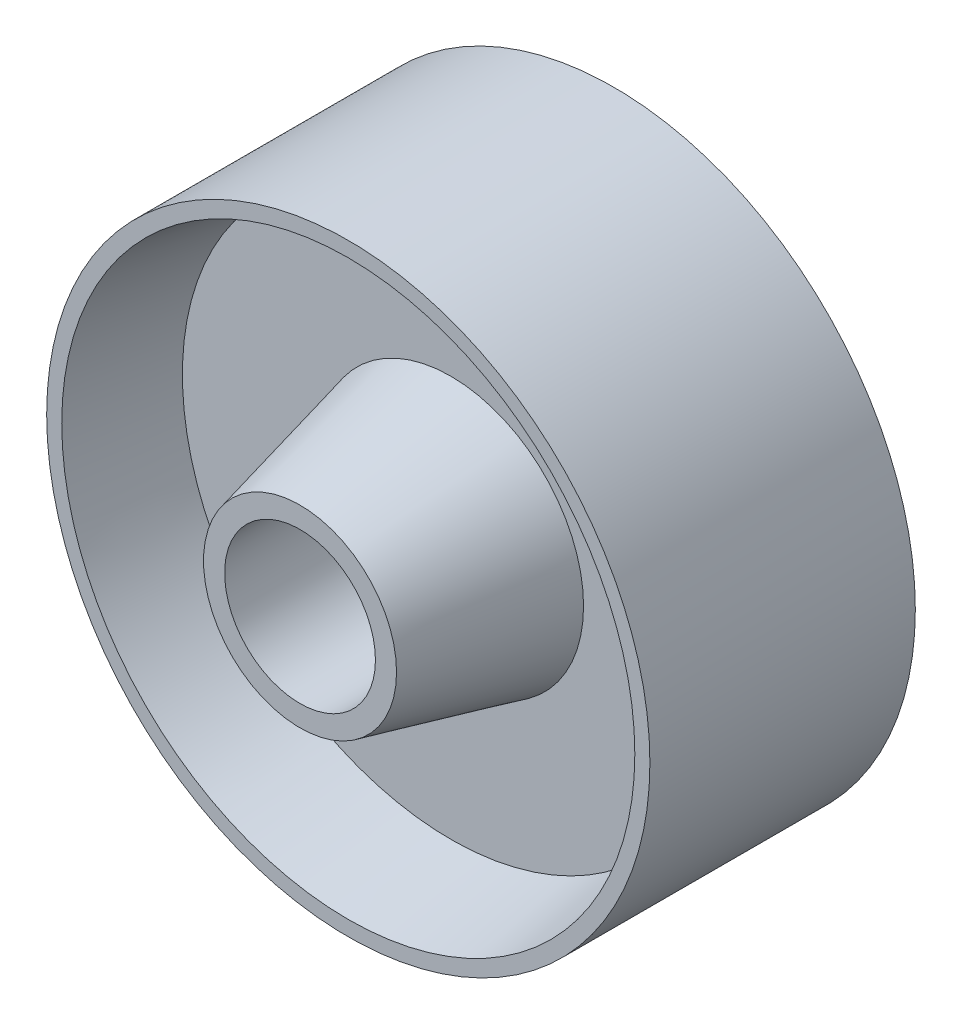
SolidWorks part; units mm, degrees
ref_plane "Front Plane" through (0, 0, 0) normal (0, 0, 1) x (1, 0, 0)
ref_plane "Top Plane" through (0, 0, 0) normal (0, 1, 0) x (1, 0, 0)
ref_plane "Right Plane" through (0, 0, 0) normal (1, 0, 0) x (0, 0, -1)
sketch "Sketch1" plane through (0, 0, 0) normal (1, 0, 0) x (0, 0, -1)
  line L1 (-30, 0) -> (30, 0)
  line L2 (30, 0) -> (30, 3.5)
  line L3 (30, 3.5) -> (5, 9.5)
  line L4 (5, 9.5) -> (5, 32)
  line L5 (5, 32) -> (22, 35)
  line L6 (22, 35) -> (22, 37.5)
  line L7 (22, 37.5) -> (-22, 37.5)
  line L8 (-22, 37.5) -> (-22, 35)
  line L9 (-22, 35) -> (-5, 32)
  line L10 (-5, 32) -> (-5, 9.5)
  line L11 (-5, 9.5) -> (-30, 3.5)
  line L12 (-30, 3.5) -> (-30, 0)
  line L13 (-51.6646, -12.5) -> (62.3218, -12.5) construction
  point P5 (0, 37.5)
  point P20 (0, 0)
  dimension "D1" = 60
  dimension "D2" = 12.5
  dimension "D3" = 3.5
  dimension "D4" = 6
  dimension "D5" = 22.5
  dimension "D6" = 3
  dimension "D7" = 2.5
  dimension "D8" = 44
  dimension "D9" = 10
revolve "Revolve1" add sketch "Sketch1" angle 360 about L13
